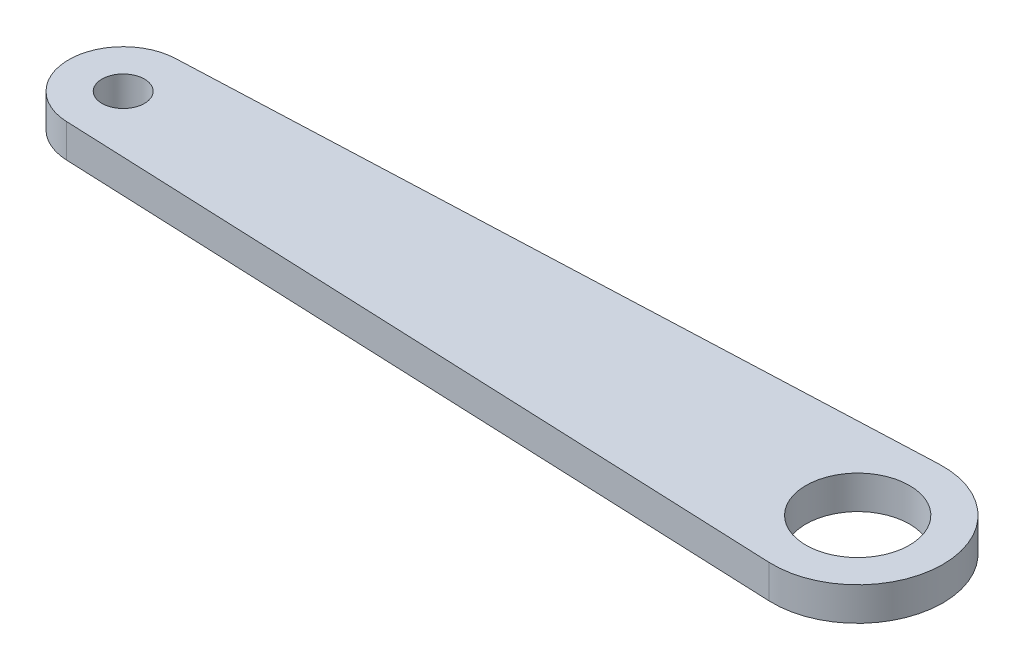
SolidWorks part; units mm, degrees
ref_plane "Front Plane" through (0, 0, 0) normal (0, 0, 1) x (1, 0, 0)
ref_plane "Top Plane" through (0, 0, 0) normal (0, 1, 0) x (1, 0, 0)
ref_plane "Right Plane" through (0, 0, 0) normal (1, 0, 0) x (0, 0, -1)
ref_plane "Plane1" through (0, 5, 0) normal (0, 1, 0) x (1, 0, 0)
sketch "Sketch1" plane through (0, 5, 0) normal (0, 1, 0) x (1, 0, 0)
  line L0 (-9.0175, -3.9517) -> (-118.8273, -8.5228)
  line L1 (-118.8273, -24.8586) -> (-9.0175, -29.4297)
  line L2 (-118.4873, -16.6907) -> (-8.4873, -16.6907) construction
  circle A0 centre (-118.4873, -16.6907) radius 3.175
  arc A1 (-9.0175, -29.4297) -> (-9.0175, -3.9517) centre (-8.4873, -16.6907) ccw
  arc A2 (-118.8273, -8.5228) -> (-118.8273, -24.8586) centre (-118.4873, -16.6907) ccw
  circle A3 centre (-8.4873, -16.6907) radius 7.75
  dimension "D1" = 15.5
  dimension "D2" = 5
  dimension "D3" = 6.35
  dimension "D4" = 5
  dimension "D5" = 110
extrude "Boss-Extrude1" add sketch "Sketch1" against normal blind 5
